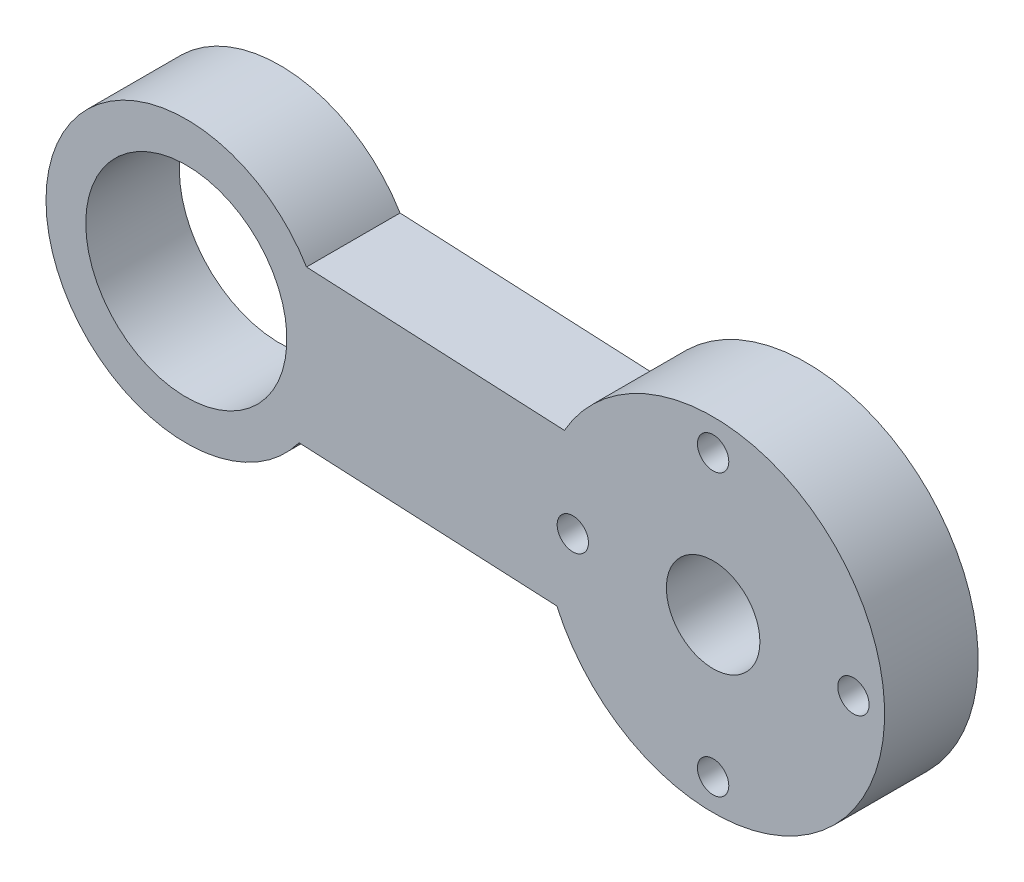
SolidWorks part; units mm, degrees
ref_plane "Plan de face" through (0, 0, 0) normal (0, 0, 1) x (1, 0, 0)
ref_plane "Plan de dessus" through (0, 0, 0) normal (0, 1, 0) x (1, 0, 0)
ref_plane "Plan de droite" through (0, 0, 0) normal (1, 0, 0) x (0, 0, -1)
sketch "Esquisse1" plane through (0, 0, 0) normal (0, 0, 1) x (1, 0, 0)
  line L1 (-10.0259, -4.5257) -> (-40.0259, -3.0709)
  line L2 (-9.541, 5.4743) -> (-39.541, 6.9291)
  line L3 (-40.0259, -3.0709) -> (-39.541, 6.9291)
  arc A0 (-10.0259, -4.5257) -> (-9.541, 5.4743) centre (0, 0) ccw
  dimension "D1" = 22
  dimension "D2" = 10
  dimension "D3" = 30
extrude "Boss.-Extru.1" add sketch "Esquisse1" along normal blind 6
sketch "Esquisse2" plane through (0, 0, 6) normal (0, 0, 1) x (1, 0, 0)
  line L2 (-40.0259, -3.0709) -> (-10.0259, -4.5257) construction
  circle A0 centre (0, 9) radius 1.005
  circle A1 centre (9, 0) radius 1.005
  circle A2 centre (0, -9) radius 1.005
  circle A3 centre (-9, 0) radius 1.005
  circle A4 centre (-33.7908, 1.6326) radius 1.005
  circle A6 centre (0, 0) radius 3
  dimension "D1" = 2.01
  dimension "D2" = 2.01
  dimension "D3" = 2.01
  dimension "D4" = 2.01
  dimension "D5" = 24.7908
  dimension "D6" = 2.01
  dimension "D7" = 6
  dimension "D8" = 9
  dimension "D9" = 9
  dimension "D10" = 9
  dimension "D11" = 9
  dimension "D12" = 5
extrude "Enlèv. mat.-Extru.1" cut sketch "Esquisse2" against normal blind 6
sketch "Esquisse3" plane through (0, 0, 0) normal (0, 0, -1) x (-1, 0, 0)
  circle A0 centre (33.7908, 1.6326) radius 9
  dimension "D1" = 18
extrude "Boss.-Extru.2" add sketch "Esquisse3" against normal blind 6
sketch "Esquisse5" plane through (0, 0, 0) normal (0, 0, -1) x (-1, 0, 0)
  circle A0 centre (33.7908, 1.6326) radius 6.45
  dimension "D1" = 12.9
extrude "Enlèv. mat.-Extru.2" cut sketch "Esquisse5" against normal blind 6
